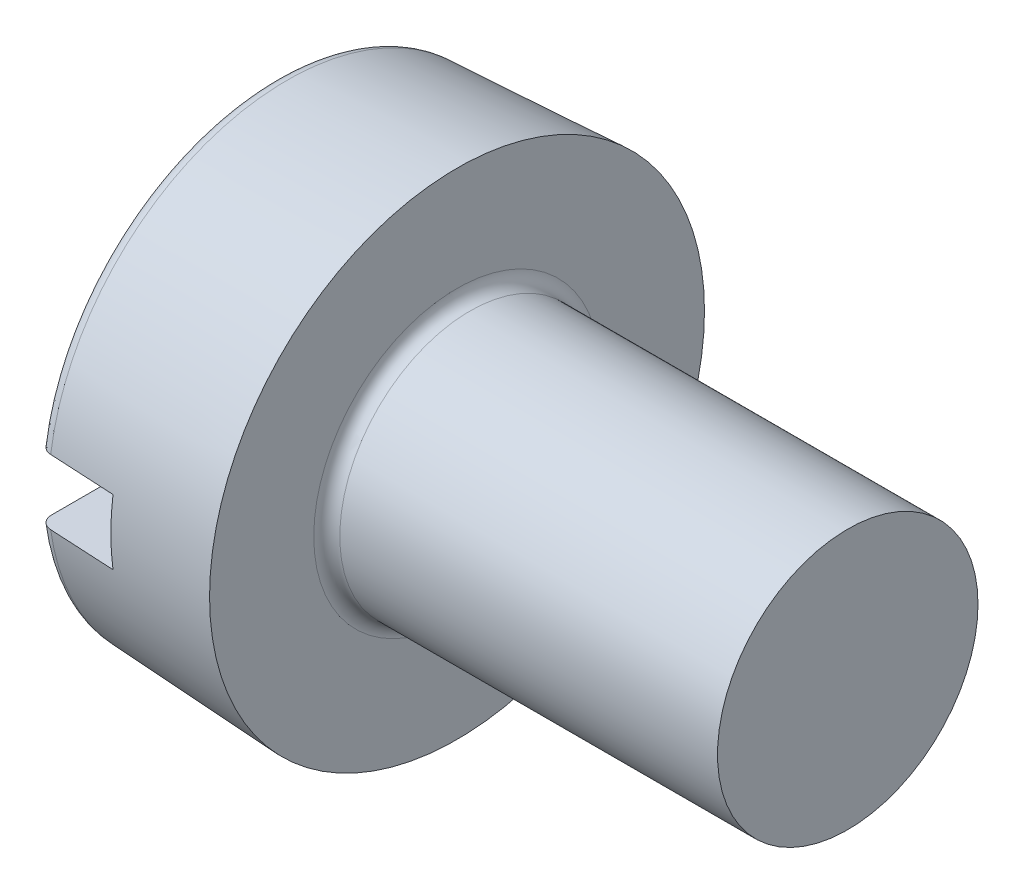
SolidWorks part; units mm, degrees
ref_plane "Front" through (0, 0, 0) normal (0, 0, 1) x (1, 0, 0)
ref_plane "Top" through (0, 0, 0) normal (0, 1, 0) x (1, 0, 0)
ref_plane "Right" through (0, 0, 0) normal (1, 0, 0) x (0, 0, -1)
other "Configuration Table"
ref_plane "Plane1" through (1.4, 0, 0) normal (1, 0, 0) x (0, 0, -1)
sketch "Sketch2" plane through (1.4, 0, 0) normal (1, 0, 0) x (0, 0, -1)
  circle A0 centre (0, 0) radius 1.9
  dimension "dk" = 3.8
extrude "BaseHead" add sketch "Sketch2" against normal blind 1.4 draft 3
sketch "Sketch3" plane through (1.4, -1.1101, -1.3544) normal (1, 0, 0) x (0, 0, -1)
  line L0 (-1.3544, 1.1101) -> (-0.5544, 1.1101) construction
  circle A0 centre (-1.3544, 1.1101) radius 1
  circle A1 centre (-1.3544, 1.1101) radius 1.9 construction
  dimension "d" = 2
  dimension "a" = 0.8
extrude "BaseBody" add sketch "Sketch3" along normal blind 3
cosmetic thread "ThreadCosmetic1" [suppressed] parameters "D1"=3, "D2"=1.567
sketch "Sketch4" plane through (-1.9, -1.9, 0) normal (0, 0, 1) x (0, 1, 0)
  line L1 (1.65, -1.9) -> (2.15, -1.9)
  line L2 (1.65, -1.9) -> (1.65, -2.5)
  line L3 (1.65, -2.5) -> (2.15, -2.5)
  line L4 (2.15, -1.9) -> (2.15, -2.5)
  line L5 (3.7266, -1.9) -> (0.0734, -1.9) construction
  dimension "n" = 0.5
  dimension "t" = 0.6
  dimension "m" = 0.25
extrude "Slot" cut sketch "Sketch4" against normal through all and the other way through all
fillet "HeadFillet" radius 0.1 3 edges at (1.4, 0, -1) (0, -1.8266, 0) (0, 1.8266, 0)
sketch "Sketch1" plane through (0, 0, 0) normal (0, 0, 1) x (1, 0, 0)
  line L0 (5.5483, 0) -> (-2.9147, 0) construction
  line L1 (1.4, 5.7835) -> (-20.6, 5.7835)
  line L2 (1.4, 5.7835) -> (1.4, 0.7835)
  line L3 (1.4, 0.7835) -> (-21.6, 0.7835)
  line L8 (-20.6, 1) -> (-21.6, 0.7835)
  line L9 (-20.6, 5.7835) -> (-20.6, 1)
  line L10 (1.4, -1.9) -> (1.4, 1.9) construction
  line L11 (4.4, -1) -> (4.4, 1) construction
  line L12 (4.4, 1) -> (1.5, 1) construction
  dimension "b1" = 1.567
  dimension "b" = 25
  dimension "x" = 1
  dimension "dd" = 5
sketch "Sketch5" plane through (0, 0, 0) normal (0, 0, 1) x (1, 0, 0)
  line L0 (4.5082, 1) -> (4.5082, 1.2165)
  line L1 (4.5082, 1.2165) -> (4.2917, 1.2165)
  line L2 (4.2917, 1.2165) -> (4.2917, 1)
  line L3 (4.2917, 1) -> (4.4, 0.8125)
  line L4 (4.4, 0.8125) -> (4.5082, 1)
  line L5 (4.4, -1) -> (4.4, 1) construction
  line L6 (0, 0) -> (15.9087, 0) construction
  dimension "D1" = 2
  dimension "D2" = 0.2165
revolve "Cut-Revolve10" [suppressed] cut sketch "Sketch5" angle 360 about L6
pattern_linear "LPattern10" [suppressed] count 12 spacing 0.2598 along (1, 0, 0)
equation "\"m@Sketch4\" = \"n@Sketch4\" / 2"
equation "\"D1@Plane1\"=\"k@BaseHead\""
equation "\"D1@Sketch5\" = \"d@Sketch3\""
equation "\"D2@Sketch5\" =  ( \"d@Sketch3\" - \"D2@ThreadCosmetic1\" )  / 2"
equation "\"D3@LPattern10\" = \"D2@Sketch5\" * 1.2"
equation "\"D1@LPattern10\" = \"D1@ThreadCosmetic1\" / \"D3@LPattern10\""
